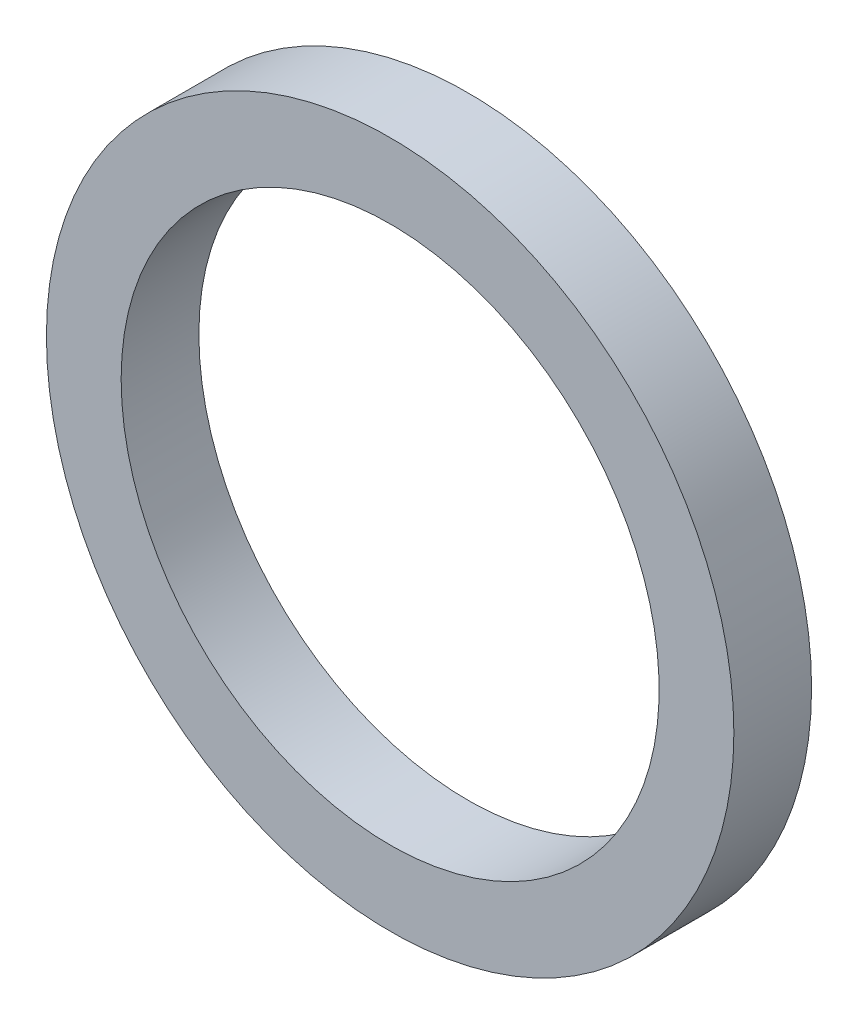
SolidWorks part; units mm, degrees
material "6061 合金"
ref_plane "前视基准面" through (0, 0, 0) normal (0, 0, 1) x (1, 0, 0)
ref_plane "上视基准面" through (0, 0, 0) normal (0, 1, 0) x (1, 0, 0)
ref_plane "右视基准面" through (0, 0, 0) normal (1, 0, 0) x (0, 0, -1)
other "Configuration Table"
sketch "草图1" plane through (0, 0, 0) normal (0, 0, 1) x (1, 0, 0)
  circle A0 centre (0, 0) radius 57.5
  circle A1 centre (0, 0) radius 45
  dimension "D1" = 90
  dimension "D2" = 115
extrude "凸台-拉伸1" add sketch "草图1" along normal blind 13
